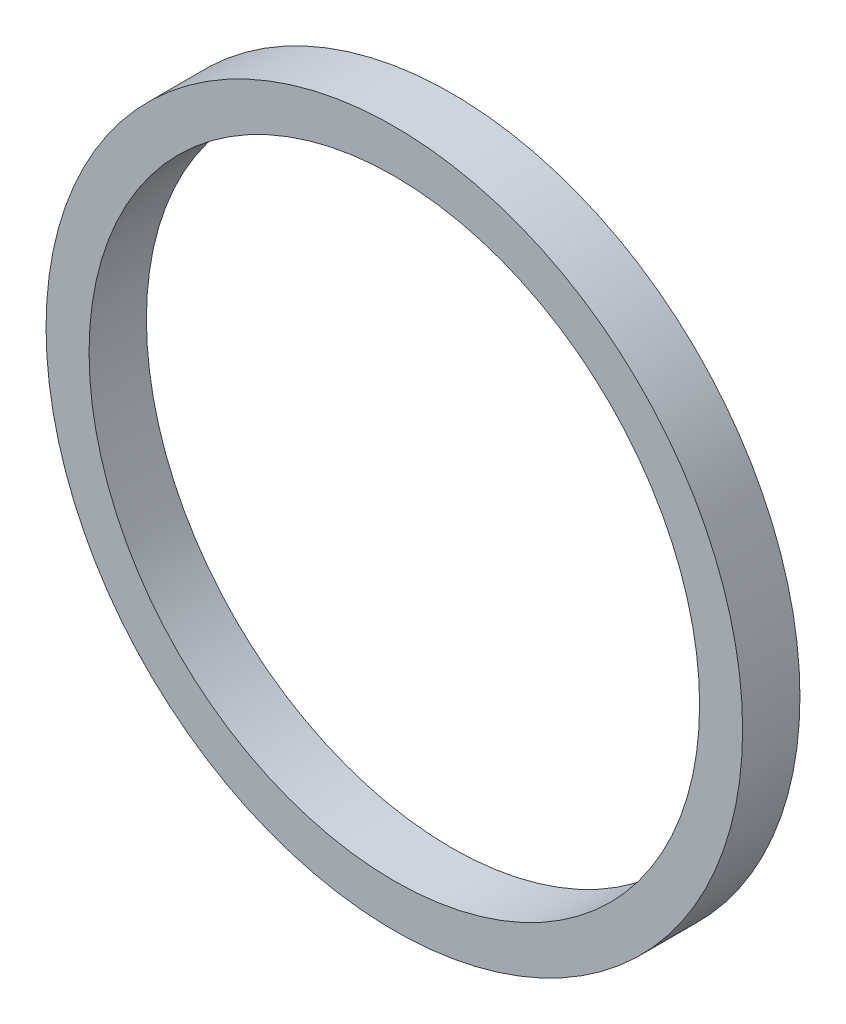
SolidWorks part; units mm, degrees
ref_plane "Спереди" through (0, 0, 0) normal (0, 0, 1) x (1, 0, 0)
ref_plane "Сверху" through (0, 0, 0) normal (0, 1, 0) x (1, 0, 0)
ref_plane "Справа" through (0, 0, 0) normal (1, 0, 0) x (0, 0, -1)
sketch "Эскиз1" plane through (0, 0, 0) normal (0, 0, 1) x (1, 0, 0)
  circle A0 centre (0, 0) radius 12.15
  circle A1 centre (0, 0) radius 10.65
  dimension "D1" = 24.3
  dimension "D2" = 1.5
extrude "Бобышка-Вытянуть1" add sketch "Эскиз1" along normal blind 2
